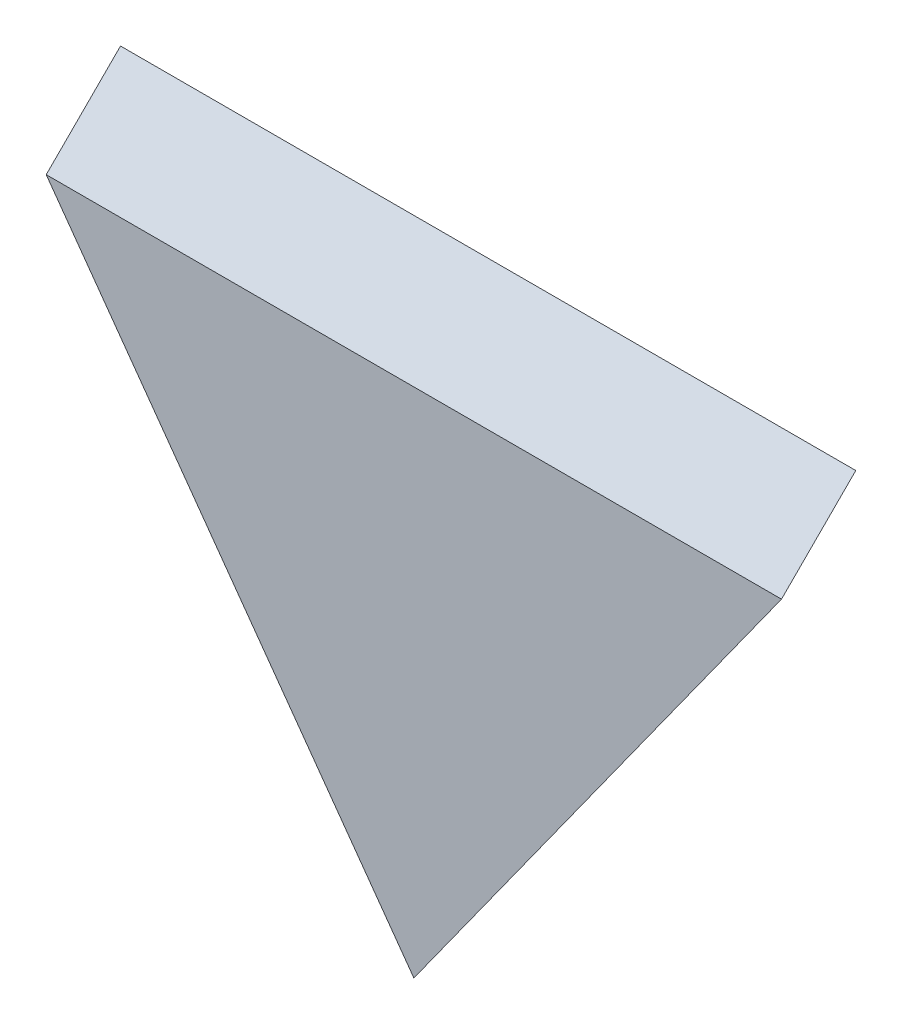
SolidWorks part; units mm, degrees
ref_plane "Front Plane" through (0, 0, 0) normal (0, 0, 1) x (1, 0, 0)
ref_plane "Top Plane" through (0, 0, 0) normal (0, 1, 0) x (1, 0, 0)
ref_plane "Right Plane" through (0, 0, 0) normal (1, 0, 0) x (0, 0, -1)
sketch "Sketch1" plane through (0, 0, 0) normal (0, 0, 1) x (1, 0, 0)
  line L0 (0, 0) -> (0, 74.1534) construction
  line L1 (0, 0) -> (44.45, 61.8921)
  line L2 (44.45, 61.8921) -> (-44.45, 61.8921)
  line L3 (0, 0) -> (-44.45, 61.8921)
  point P6 (0, 61.8921)
  dimension "D1" = 76.2
  dimension "D2" = 44.45
sketch "Sketch2" plane through (0, 0, 0) normal (1, 0, 0) x (0, 0, -1)
  line L0 (0, 0) -> (30.3962, 0) construction
  line L1 (0, 0) -> (8.9803, 8.9803)
  dimension "D1" = 45
  dimension "D2" = 12.7
sweep "Sweep1" add profiles "Sketch1" path "Sketch2"
